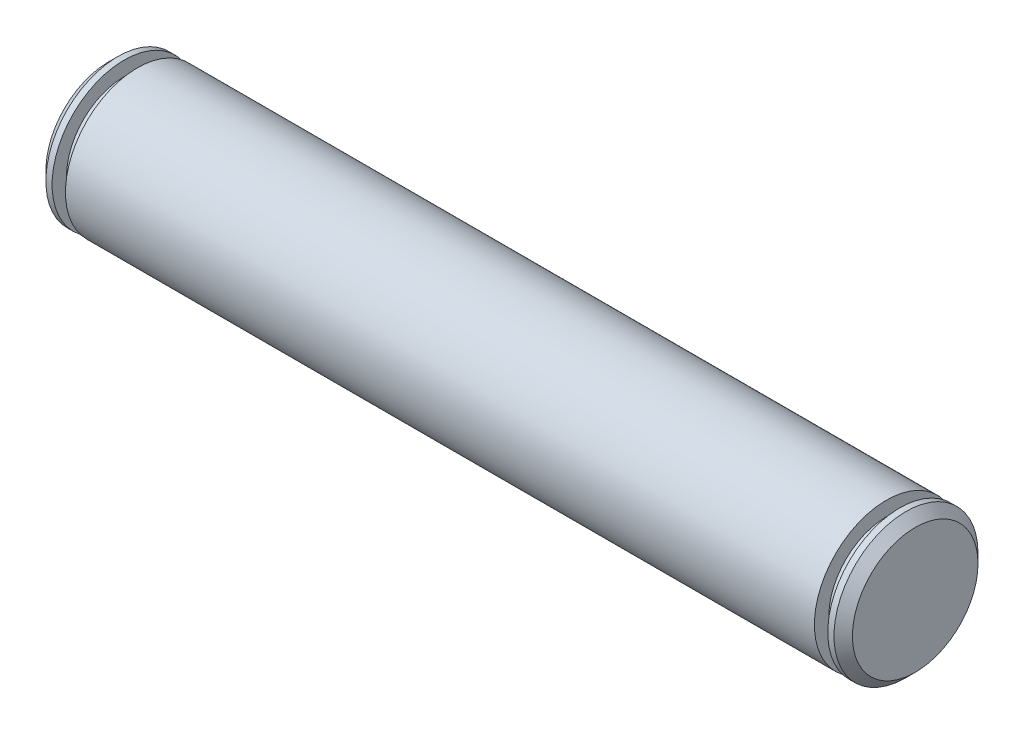
SolidWorks part; units mm, degrees
ref_plane "Front Plane" through (0, 0, 0) normal (0, 0, 1) x (1, 0, 0)
ref_plane "Top Plane" through (0, 0, 0) normal (0, 1, 0) x (1, 0, 0)
ref_plane "Right Plane" through (0, 0, 0) normal (1, 0, 0) x (0, 0, -1)
sketch "Sketch1" plane through (0, 0, 0) normal (1, 0, 0) x (0, 0, -1)
  circle A0 centre (0, 0) radius 3.9688
  dimension "D1" = 7.9375
extrude "Boss-Extrude1" add sketch "Sketch1" along normal mid plane 44.45
chamfer "Chamfer1" distance 0.508 angle 45 2 edges at (-22.225, 0, -3.9688) (22.225, 0, -3.9688)
ref_plane "Plane1" through (20.6375, 0, 0) normal (1, 0, 0) x (0, 0, -1)
sketch "Sketch2" plane through (20.6375, 0, 0) normal (1, 0, 0) x (0, 0, -1)
  circle A0 centre (0, 0) radius 3.9688 construction
  circle A1 centre (0, 0) radius 3.9688
  circle A2 centre (0, 0) radius 3.175
  dimension "D1" = 6.35
extrude "Cut-Extrude1" cut sketch "Sketch2" along normal blind 0.7366
mirror "Mirror1" about plane through (0, 0, 0) normal (1, 0, 0) of "Cut-Extrude1"
